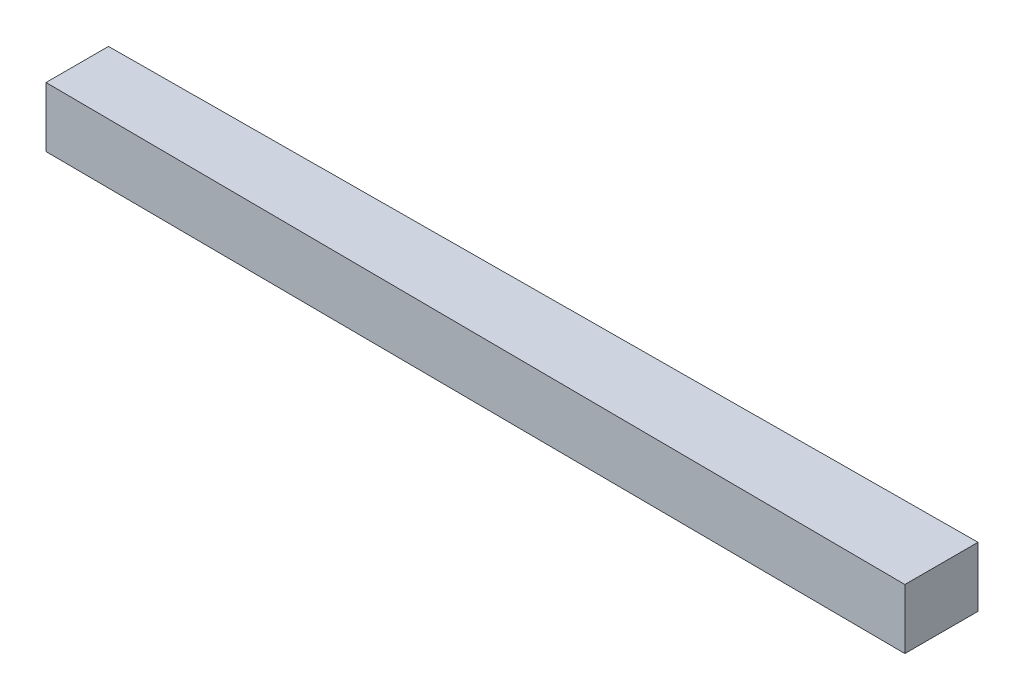
SolidWorks part; units mm, degrees
material "1023 Carbon Steel Sheet (SS)"
ref_plane "Front Plane" through (0, 0, 0) normal (0, 0, 1) x (1, 0, 0)
ref_plane "Top Plane" through (0, 0, 0) normal (0, 1, 0) x (1, 0, 0)
ref_plane "Right Plane" through (0, 0, 0) normal (1, 0, 0) x (0, 0, -1)
sketch "Sketch1" plane through (0, 0, 0) normal (0, 1, 0) x (1, 0, 0)
  line L0 (-32.5, 0) -> (32.5, 0) construction
  line L8 (-32.5, -2.35) -> (-32.5, 2.35)
  line L9 (-32.5, 2.35) -> (32.5, 2.75)
  line L10 (32.5, 2.75) -> (32.5, -2.75)
  line L11 (-32.5, -2.35) -> (32.5, -2.75)
  point P2 (0, 0)
  dimension "D1" = 2.35
  dimension "D2" = 2.75
  dimension "D3" = 65
extrude "Boss-Extrude1" add sketch "Sketch1" along normal blind 4.5
